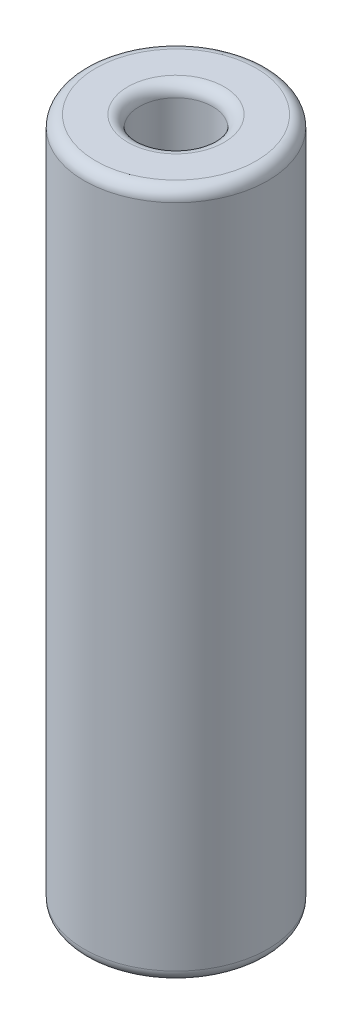
SolidWorks part; units mm, degrees
ref_plane "Front Plane" through (0, 0, 0) normal (0, 0, 1) x (1, 0, 0)
ref_plane "Top Plane" through (0, 0, 0) normal (0, 1, 0) x (1, 0, 0)
ref_plane "Right Plane" through (0, 0, 0) normal (1, 0, 0) x (0, 0, -1)
sketch "Sketch1" plane through (0, 0, 0) normal (0, 1, 0) x (1, 0, 0)
  circle A0 centre (0, 0) radius 5.08
  circle A1 centre (0, 0) radius 2.032
  dimension "D1" = 4.064
  dimension "D2" = 10.16
extrude "Boss-Extrude1" add sketch "Sketch1" along normal blind 38.1
fillet "Fillet1" radius 0.635 4 edges at (0, 0, 2.032) (0, 0, 5.08) (0, 38.1, 2.032) (0, 38.1, 5.08)
